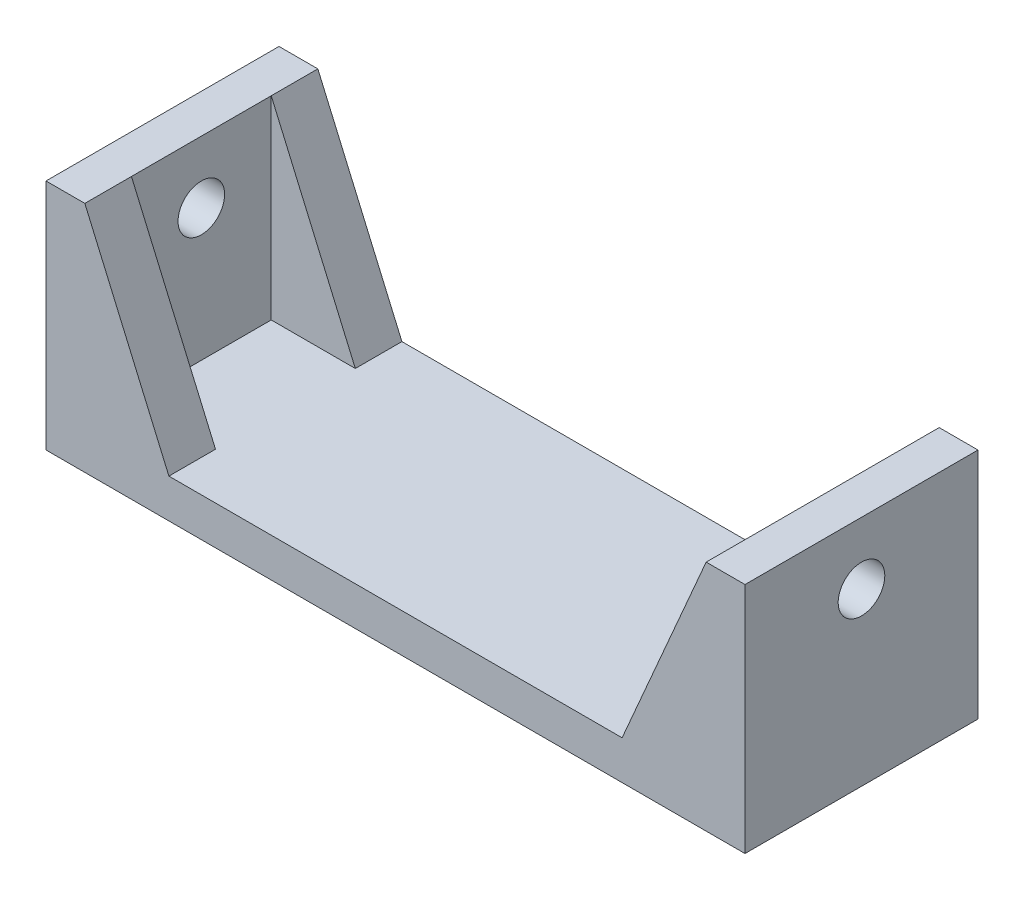
SolidWorks part; units mm, degrees
ref_plane "Front Plane" through (0, 0, 0) normal (0, 0, 1) x (1, 0, 0)
ref_plane "Top Plane" through (0, 0, 0) normal (0, 1, 0) x (1, 0, 0)
ref_plane "Right Plane" through (0, 0, 0) normal (1, 0, 0) x (0, 0, -1)
sketch "Sketch1" plane through (0, 0, 0) normal (0, 1, 0) x (1, 0, 0)
  line L1 (0, 0) -> (90, 0)
  line L2 (0, 0) -> (0, 30)
  line L3 (0, 30) -> (90, 30)
  line L4 (90, 0) -> (90, 30)
  dimension "D1" = 90
  dimension "D2" = 30
extrude "Boss-Extrude1" add sketch "Sketch1" along normal blind 30
shell "Shell1" thickness 5
sketch "Sketch2" plane through (90, 0, 0) normal (1, 0, 0) x (0, 0, -1)
  line L0 (0, 30) -> (30, 30) construction
  line L1 (0, 30) -> (0, 0) construction
  circle A0 centre (15, 22) radius 3
  dimension "D1" = 6
  dimension "D3" = 15
  dimension "D2" = 8
extrude "Cut-Extrude1" cut sketch "Sketch2" against normal through all both and the other way through all
sketch "Sketch4" plane through (0, 0, 0) normal (0, 0, 1) x (1, 0, 0)
  line L0 (5, 30) -> (15.8251, 5)
  line L1 (5, 5) -> (85, 5) construction
rib "Rib1" sketch "Sketch4" sketch "Sketch4" thickness 6 extrusion direction parallel to sketch draft on no parameters "D1"=6
ref_plane "Plane1" through (45, 0, 0) normal (1, 0, 0) x (0, 0, -1)
ref_plane "Plane2" through (0, 0, -15) normal (0, 0, 1) x (1, 0, 0)
mirror "Mirror1" about plane through (45, 0, 0) normal (1, 0, 0) of "Rib1"
mirror "Mirror2" about plane through (0, 0, -15) normal (0, 0, 1) of "Mirror1", "Rib1"
